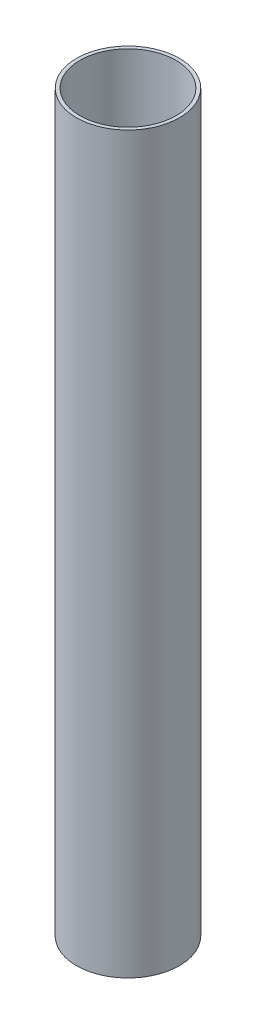
SolidWorks part; units mm, degrees
ref_plane "Front Plane" through (0, 0, 0) normal (0, 0, 1) x (1, 0, 0)
ref_plane "Top Plane" through (0, 0, 0) normal (0, 1, 0) x (1, 0, 0)
ref_plane "Right Plane" through (0, 0, 0) normal (1, 0, 0) x (0, 0, -1)
sketch "Sketch1" plane through (0, 0, 0) normal (0, 1, 0) x (1, 0, 0)
  circle A0 centre (0, 0) radius 49.2125
  circle A1 centre (0, 0) radius 45.9359
  dimension "D1" = 98.425
  dimension "D2" = 3.2766
extrude "Boss-Extrude1" add sketch "Sketch1" along normal blind 702.056
